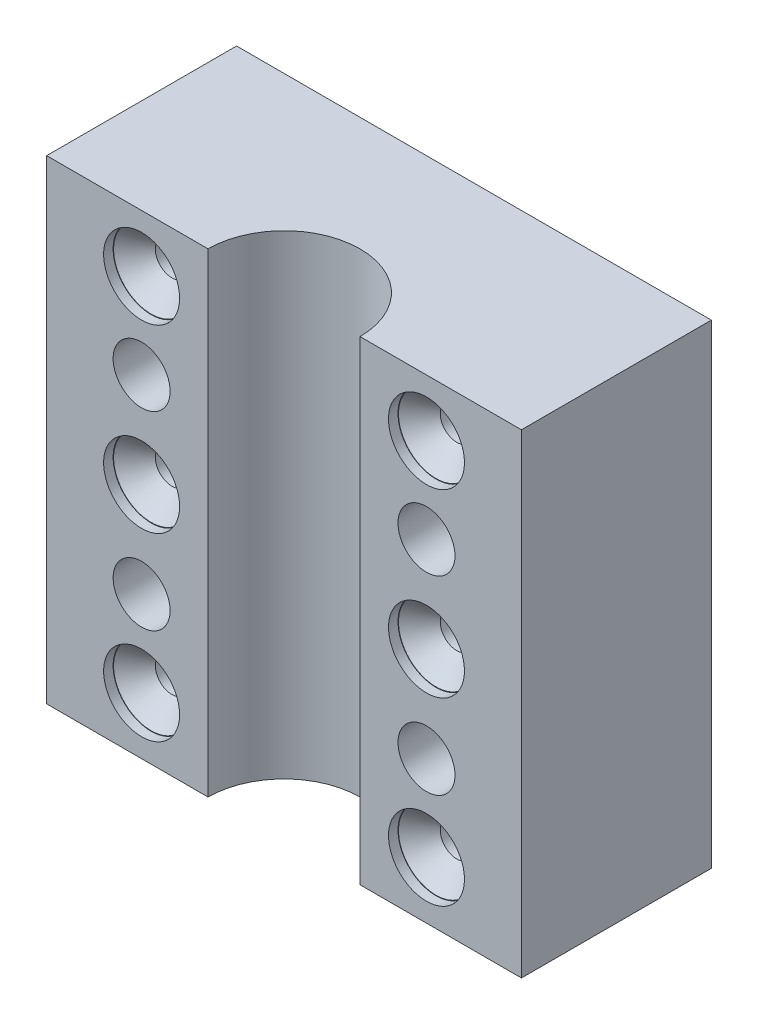
SolidWorks part; units mm, degrees
ref_plane "Front Plane" through (0, 0, 0) normal (0, 0, 1) x (1, 0, 0)
ref_plane "Top Plane" through (0, 0, 0) normal (0, 1, 0) x (1, 0, 0)
ref_plane "Right Plane" through (0, 0, 0) normal (1, 0, 0) x (0, 0, -1)
sketch "Sketch1" plane through (0, 0, 0) normal (0, 0, 1) x (1, 0, 0)
  line L1 (0, 0) -> (50, 0)
  line L2 (0, 0) -> (0, 50)
  line L3 (0, 50) -> (50, 50)
  line L4 (50, 0) -> (50, 50)
  dimension "D1" = 50
  dimension "D2" = 50
extrude "Boss-Extrude1" add sketch "Sketch1" along normal blind 20
sketch "Sketch2" plane through (0, 50, 0) normal (0, 1, 0) x (1, 0, 0)
  line L0 (50, -20) -> (0, -20) construction
  circle A0 centre (25, -20) radius 8
  dimension "D1" = 16
extrude "Cut-Extrude1" cut sketch "Sketch2" against normal blind 67.9422
sketch "Sketch3" plane through (0, 0, 20) normal (0, 0, 1) x (1, 0, 0)
  line L0 (17, 50) -> (0, 50) construction
  line L1 (0, 0) -> (17, 0) construction
  line L2 (33, 0) -> (50, 0) construction
  line L3 (50, 50) -> (33, 50) construction
  line L4 (0, 50) -> (0, 0) construction
  line L5 (50, 0) -> (50, 50) construction
  circle A0 centre (10, 35) radius 3
  circle A1 centre (10, 15) radius 3
  circle A2 centre (40, 35) radius 3
  circle A3 centre (40, 15) radius 3
  dimension "D1" = 6
  dimension "D2" = 6
  dimension "D3" = 6
  dimension "D4" = 6
  dimension "D5" = 15
  dimension "D7" = 15
  dimension "D8" = 15
  dimension "D9" = 10
  dimension "D10" = 10
  dimension "D11" = 10
  dimension "D12" = 10
  dimension "D6" = 15
extrude "Cut-Extrude2" cut sketch "Sketch3" against normal blind 43
sketch "Sketch6" plane through (0, 0, 0) normal (0, 0, -1) x (-1, 0, 0)
  line L0 (0, 0) -> (-50, 0) construction
  line L1 (-3.9378, 15) -> (-6.9689, 20.25)
  line L2 (-6.9689, 20.25) -> (-13.0311, 20.25)
  line L3 (-13.0311, 20.25) -> (-16.0622, 15)
  line L4 (-16.0622, 15) -> (-13.0311, 9.75)
  line L5 (-13.0311, 9.75) -> (-6.9689, 9.75)
  line L6 (-6.9689, 9.75) -> (-3.9378, 15)
  line L7 (-43.0311, 20.25) -> (-46.0622, 15)
  line L8 (-46.0622, 15) -> (-43.0311, 9.75)
  line L9 (-43.0311, 9.75) -> (-36.9689, 9.75)
  line L10 (-36.9689, 9.75) -> (-33.9378, 15)
  line L11 (-33.9378, 15) -> (-36.9689, 20.25)
  line L12 (-36.9689, 20.25) -> (-43.0311, 20.25)
  line L13 (-36.9689, 29.75) -> (-33.9378, 35)
  line L14 (-33.9378, 35) -> (-36.9689, 40.25)
  line L15 (-36.9689, 40.25) -> (-43.0311, 40.25)
  line L16 (-43.0311, 40.25) -> (-46.0622, 35)
  line L17 (-46.0622, 35) -> (-43.0311, 29.75)
  line L18 (-43.0311, 29.75) -> (-36.9689, 29.75)
  line L19 (-6.9689, 29.75) -> (-3.9378, 35)
  line L20 (-3.9378, 35) -> (-6.9689, 40.25)
  line L21 (-6.9689, 40.25) -> (-13.0311, 40.25)
  line L22 (-13.0311, 40.25) -> (-16.0622, 35)
  line L23 (-16.0622, 35) -> (-13.0311, 29.75)
  line L24 (-13.0311, 29.75) -> (-6.9689, 29.75)
  line L25 (-50, 50) -> (0, 50) construction
  circle A0 centre (-10, 15) radius 5.25 construction
  circle A1 centre (-40, 15) radius 5.25 construction
  circle A2 centre (-40, 35) radius 5.25 construction
  circle A3 centre (-10, 35) radius 5.25 construction
  point P28 (-10, 20.25)
  dimension "D1" = 10.5
  dimension "D2" = 10.5
  dimension "D3" = 10.5
  dimension "D4" = 10.5
  dimension "D5" = 0
  dimension "D6" = 0
  dimension "D7" = 0
  dimension "D8" = 0
extrude "Cut-Extrude5" cut sketch "Sketch6" against normal blind 5
sketch "Sketch7" plane through (0, 0, 20) normal (0, 0, 1) x (1, 0, 0)
  line L0 (0, 50) -> (0, 0) construction
  line L1 (17, 50) -> (0, 50) construction
  line L2 (0, 0) -> (17, 0) construction
  line L3 (33, 0) -> (50, 0) construction
  line L4 (50, 50) -> (33, 50) construction
  line L5 (50, 0) -> (50, 50) construction
  circle A0 centre (10, 6) radius 1.75
  circle A1 centre (10, 25) radius 1.75
  circle A2 centre (10, 44) radius 1.75
  circle A3 centre (40, 44) radius 1.75
  circle A4 centre (40, 25) radius 1.75
  circle A5 centre (40, 6) radius 1.75
  dimension "D1" = 3.5
  dimension "D2" = 3.5
  dimension "D3" = 3.5
  dimension "D4" = 3.5
  dimension "D5" = 3.5
  dimension "D6" = 3.5
  dimension "D7" = 10
  dimension "D8" = 10
  dimension "D9" = 10
  dimension "D10" = 6
  dimension "D11" = 6
  dimension "D12" = 25
  dimension "D13" = 6
  dimension "D14" = 25
  dimension "D15" = 6
  dimension "D16" = 10
  dimension "D17" = 10
  dimension "D18" = 10
extrude "Cut-Extrude6" cut sketch "Sketch7" against normal blind 41
sketch "Sketch9" plane through (0, 0, 20) normal (0, 0, 1) x (1, 0, 0)
  circle A0 centre (10, 44) radius 4
  circle A1 centre (10, 25) radius 4
  circle A2 centre (10, 6) radius 4
  circle A3 centre (40, 6) radius 4
  circle A4 centre (40, 25) radius 4
  circle A5 centre (40, 44) radius 4
  dimension "D1" = 8
  dimension "D2" = 8
  dimension "D3" = 8
  dimension "D4" = 8
  dimension "D5" = 8
  dimension "D6" = 8
extrude "Cut-Extrude7" cut sketch "Sketch9" against normal blind 1
chamfer "Chamfer1" distance 2.2 angle 45 6 edges at (41.75, 6, 19) (11.75, 25, 19) (11.75, 6, 19) (41.75, 25, 19) (41.75, 44, 19) (11.75, 44, 19)
